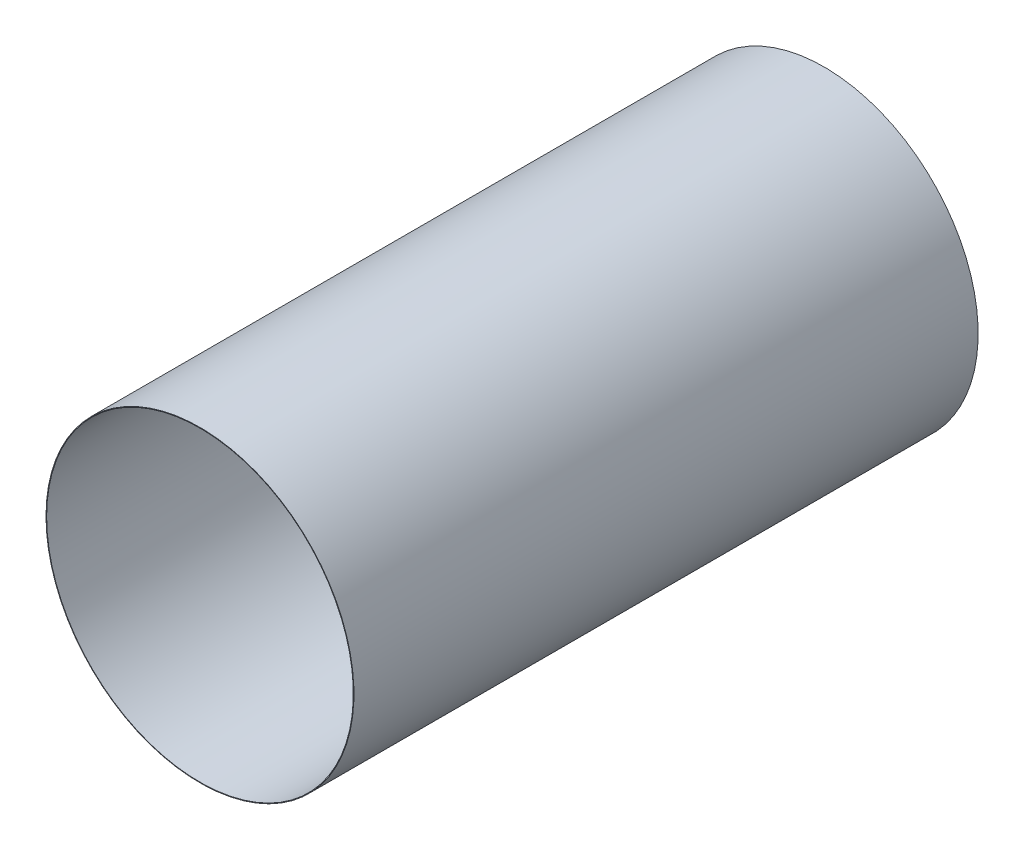
SolidWorks part; units mm, degrees
material "Silicon"
ref_plane "Ebene vorne" through (0, 0, 0) normal (0, 0, 1) x (1, 0, 0)
ref_plane "Ebene oben" through (0, 0, 0) normal (0, 1, 0) x (1, 0, 0)
ref_plane "Ebene rechts" through (0, 0, 0) normal (1, 0, 0) x (0, 0, -1)
sketch "Sketch1" plane through (0, 0, 0) normal (0, 0, 1) x (1, 0, 0)
  circle A0 centre (0, 0) radius 51.1
  circle A1 centre (0, 0) radius 51.3
  dimension "D1" = 102.2
  dimension "D2" = 0.2
extrude "Boss-Extrude1" add sketch "Sketch1" along normal blind 208
